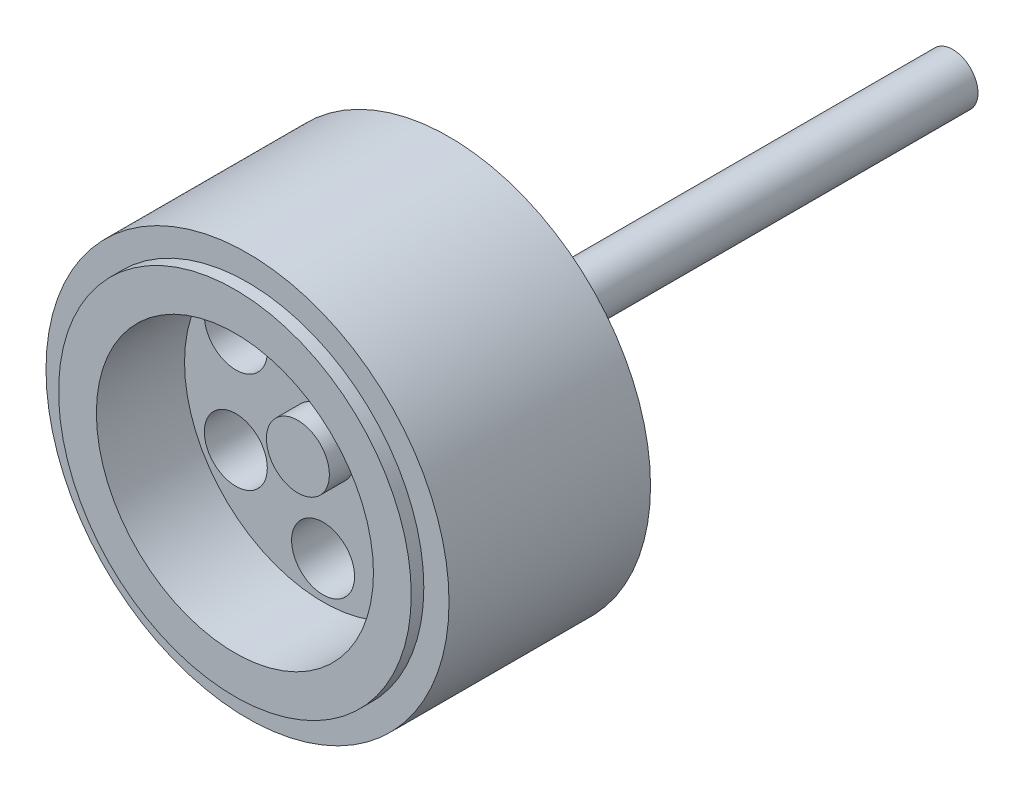
SolidWorks part; units mm, degrees
ref_plane "Front Plane" through (0, 0, 0) normal (0, 0, 1) x (1, 0, 0)
ref_plane "Top Plane" through (0, 0, 0) normal (0, 1, 0) x (1, 0, 0)
ref_plane "Right Plane" through (0, 0, 0) normal (1, 0, 0) x (0, 0, -1)
sketch "Sketch1" plane through (0, 0, 0) normal (1, 0, 0) x (0, 0, -1)
  line L0 (0, 0) -> (141.0669, 0) construction
  line L1 (0, 4) -> (0, 22)
  line L2 (0, 22) -> (-14, 22)
  line L3 (-14, 22) -> (-14, 28)
  line L4 (-14, 28) -> (-12, 28)
  line L5 (-12, 28) -> (-12, 26)
  line L8 (20, 22) -> (8, 22)
  line L9 (8, 22) -> (8, 10)
  line L10 (8, 10) -> (20, 10)
  line L11 (22, 10) -> (22, 4)
  line L12 (20, 4) -> (0, 4)
  line L17 (-12, 26) -> (20, 26)
  line L18 (20, 26) -> (20, 28)
  line L19 (20, 28) -> (22, 28)
  line L20 (22, 28) -> (22, 22)
  line L21 (20, 32) -> (-12, 32) construction
  line L22 (20, 26) -> (20, 22) construction
  line L23 (20, 22) -> (22, 22)
  line L24 (20, 10) -> (20, 4) construction
  line L25 (20, 10) -> (22, 10)
  line L26 (20, 4) -> (22, 4)
  dimension "D1" = 4
  dimension "D2" = 32
  dimension "D3" = 2
  dimension "D4" = 2
  dimension "D5" = 32
  dimension "D6" = 4
  dimension "D7" = 8
  dimension "D8" = 10
  dimension "D9" = 12
  dimension "D10" = 22
  dimension "D13" = 6
revolve "Revolve1" add sketch "Sketch1" angle 360 about L0
sketch "Sketch3" plane through (0, 0, 0) normal (1, 0, 0) x (0, 0, -1)
  line L0 (-11.999, 32) -> (-11.999, 26.001)
  line L1 (-11.999, 26.001) -> (19.999, 26.001)
  line L2 (19.999, 26.001) -> (19.999, 32)
  line L3 (19.999, 32) -> (-11.999, 32)
  line L4 (20, 26) -> (-12, 26) construction
  line L5 (-12, -28) -> (-12, 28) construction
  line L8 (0, 0) -> (22, 0) construction
  line L9 (22, -4) -> (22, 4) construction
  dimension "D1" = 0.001
  dimension "D2" = 0.001
  dimension "D3" = 31.998
  dimension "D4" = 32
revolve "Revolve2" add sketch "Sketch3" angle 360 about L8
sketch "Sketch2" plane through (0, 0, 0) normal (0, 0, 1) x (1, 0, 0)
  line L0 (0, 16) -> (0, 0) construction
  circle A0 centre (0, 16) radius 5
  circle A1 centre (13.8564, 8) radius 5
  circle A2 centre (13.8564, -8) radius 5
  circle A3 centre (0, -16) radius 5
  circle A4 centre (-13.8564, -8) radius 5
  circle A5 centre (-13.8564, 8) radius 5
  point P16 (0, 0)
  dimension "D1" = 10
  dimension "D2" = 16
extrude "Cut-Extrude1" cut sketch "Sketch2" against normal up to surface (8 mm away) up to face at (22, 0, -8)
sketch "Sketch4" plane through (0, 0, 0) normal (1, 0, 0) x (0, 0, -1)
  line L0 (0, 4) -> (0, -4) construction
  line L1 (0, 9.6803) -> (0, -13.224) construction
  line L2 (0, 0) -> (38.2315, 0) construction
  line L3 (-0.001, 4) -> (-0.001, 5)
  line L4 (-0.001, 5) -> (-4.001, 5)
  line L5 (-4.001, 5) -> (-4.001, 0)
  line L6 (-0.001, 4) -> (99.999, 4)
  line L7 (99.999, 4) -> (99.999, 0)
  line L8 (-4.001, 0) -> (99.999, 0)
  dimension "D1" = 5
  dimension "D2" = 4
  dimension "D3" = 0.001
  dimension "D4" = 4
  dimension "D5" = 100
revolve "Revolve3" add sketch "Sketch4" angle 360 about L8
